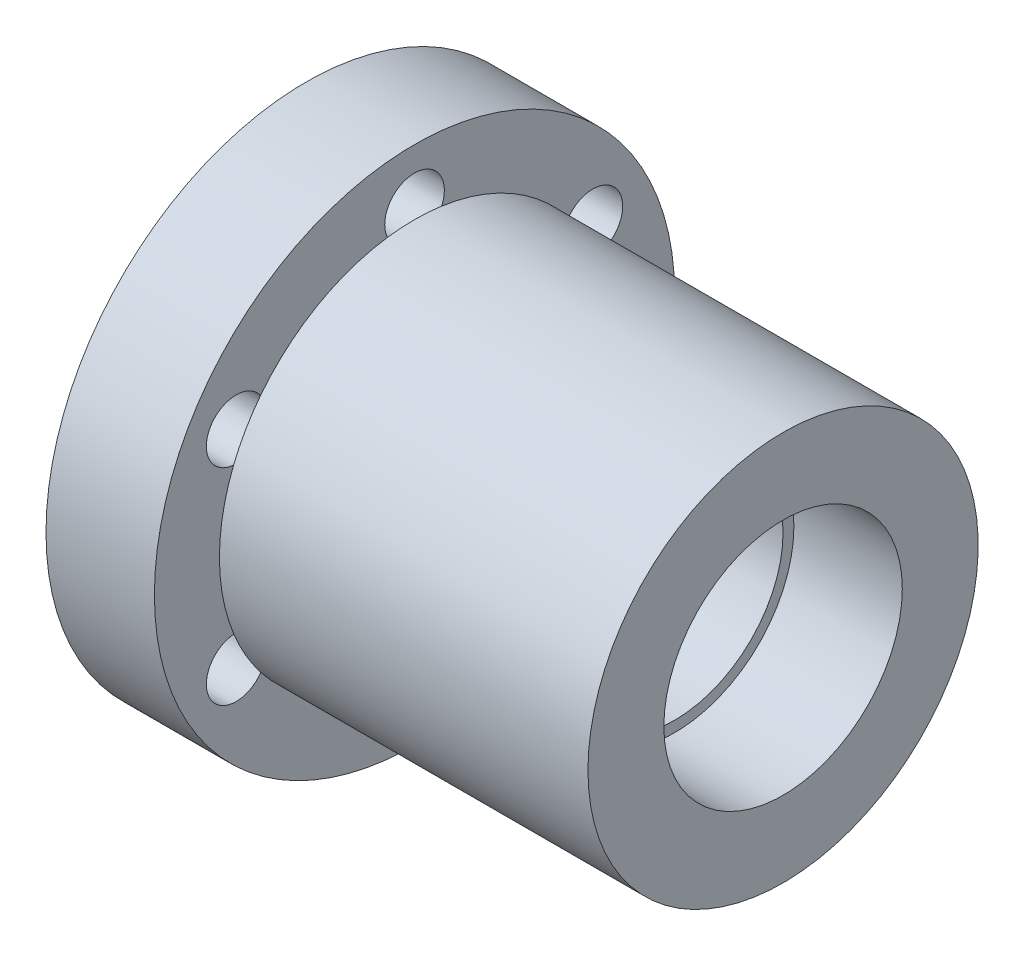
SolidWorks part; units mm, degrees
ref_plane "Front Plane" through (0, 0, 0) normal (0, 0, 1) x (1, 0, 0)
ref_plane "Top Plane" through (0, 0, 0) normal (0, 1, 0) x (1, 0, 0)
ref_plane "Right Plane" through (0, 0, 0) normal (1, 0, 0) x (0, 0, -1)
sketch "Sketch1" plane through (0, 0, 0) normal (0, 0, 1) x (1, 0, 0)
  line L0 (0, 0) -> (0, 37.1823) construction
  line L1 (0, 0) -> (47.7812, 0) construction
  line L2 (10, 0) -> (10, 6)
  line L3 (10, 6) -> (44, 6)
  line L4 (44, 6) -> (44, 13)
  line L5 (44, 13) -> (34, 13)
  line L6 (34, 13) -> (34, 14)
  line L7 (34, 14) -> (10, 14)
  line L8 (10, 14) -> (10, 13)
  line L9 (10, 13) -> (0, 13)
  line L10 (0, 13) -> (0, 0)
  line L11 (0, 0) -> (10, 0)
  line L12 (0, 24) -> (48.4688, 24) construction
  point P3 (34, 13.5)
  dimension "D1" = 44
  dimension "D2" = 24
  dimension "D3" = 10
  dimension "D4" = 10
  dimension "D5" = 10
  dimension "D6" = 11
  dimension "D7" = 11
  dimension "D8" = 24
  dimension "D9" = 6
revolve "Revolve1" add sketch "Sketch1" angle 360 about L12
sketch "Sketch2" plane through (0, 0, 0) normal (-1, 0, 0) x (0, 0, 1)
  line L0 (0, 24) -> (0, 48) construction
  line L1 (0, 48) -> (0, 24) construction
  line L2 (0, 24) -> (0, 0) construction
  line L3 (0, 24) -> (-50000, 24) construction
  circle A0 centre (0, 24) radius 24 construction
  circle A1 centre (0, 24) radius 19 construction
  circle A2 centre (0, 42.972) radius 2.75
  circle A3 centre (16.4545, 33.472) radius 2.75
  circle A4 centre (16.4545, 14.472) radius 2.75
  circle A5 centre (0, 4.972) radius 2.75
  circle A6 centre (-16.4545, 14.472) radius 2.75
  circle A7 centre (-16.4545, 33.472) radius 2.75
  point P25 (0, 23.972)
  dimension "D1" = 38
  dimension "D2" = 5.5
  dimension "D3" = 6
extrude "Cut-Extrude1" cut sketch "Sketch2" against normal blind 10
sketch "Sketch3" plane through (0, 0, 0) normal (-1, 0, 0) x (0, 0, 1)
  line L0 (-20, 39) -> (20, 39)
  line L1 (20, 39) -> (20, 9)
  line L2 (-20, 39) -> (-20, 9)
  line L3 (-20, 9) -> (20, 9)
  line L4 (0, 24) -> (10, 24)
  line L5 (0, 24) -> (0, 34) construction
  line L6 (-20, 39) -> (-9.4769, 52.5961)
  line L7 (-9.4769, 52.5961) -> (18.0723, 49.4004)
  line L8 (18.0723, 49.4004) -> (20, 39)
  line L9 (-20, 9) -> (-5.9506, -10.1059)
  line L10 (-5.9506, -10.1059) -> (23.6923, 0)
  line L11 (23.6923, 0) -> (20, 9)
  circle A0 centre (0, 24) radius 10 construction
  dimension "D1" = 40
  dimension "D2" = 30
  dimension "D3" = 15
  dimension "D4" = 20
